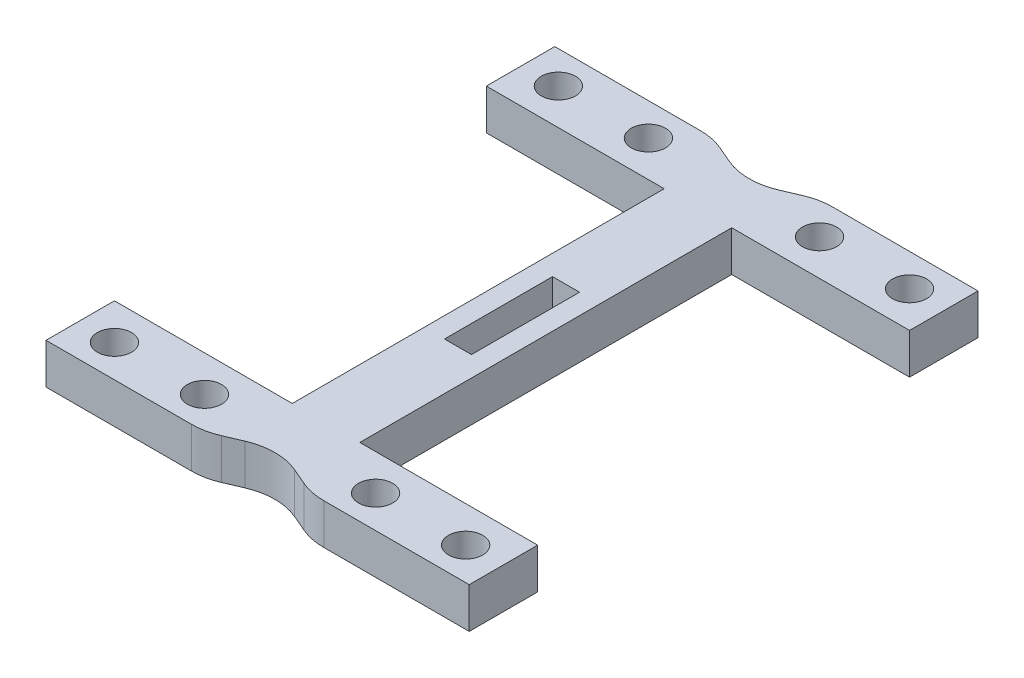
SolidWorks part; units mm, degrees
ref_plane "Front Plane" through (0, 0, 0) normal (0, 0, 1) x (1, 0, 0)
ref_plane "Top Plane" through (0, 0, 0) normal (0, 1, 0) x (1, 0, 0)
ref_plane "Right Plane" through (0, 0, 0) normal (1, 0, 0) x (0, 0, -1)
sketch "Sketch1" plane through (0, 0, 0) normal (0, 1, 0) x (1, 0, 0)
  line L0 (0, 3.6) -> (49, 3.6) construction
  line L1 (0, 0) -> (17.5879, 0)
  line L2 (0, 0) -> (0, 7.6)
  line L3 (0, 7.6) -> (19.75, 7.6)
  line L4 (47, 0) -> (47, 7.6)
  line L8 (29.4121, 0) -> (47, 0)
  line L9 (19.75, 7.6) -> (19.75, 28.25)
  line L15 (27.25, 28.25) -> (27.25, 7.6)
  line L16 (27.25, 7.6) -> (47, 7.6)
  line L17 (-0.2, 28.25) -> (47.2, 28.25) construction
  line L20 (19.75, 28.25) -> (22, 28.25)
  line L21 (17.5879, 0) -> (23.5, 2.5337)
  line L22 (23.5, 2.5337) -> (29.4121, 0)
  line L23 (19.75, 7.6) -> (27.25, 7.6) construction
  line L24 (23.5, 7.6) -> (23.5, 2.5337) construction
  line L25 (22, 28.25) -> (22, 22.25)
  line L26 (22, 22.25) -> (25, 22.25)
  line L27 (25, 22.25) -> (25, 28.25)
  line L28 (25, 28.25) -> (27.25, 28.25)
  circle A0 centre (4, 3.6) radius 1.9
  circle A1 centre (14, 3.6) radius 1.9
  circle A2 centre (33, 3.6) radius 1.9
  circle A3 centre (43, 3.6) radius 1.9
  dimension "D1" = 3.8
  dimension "D2" = 10
  dimension "D3" = 4
  dimension "D4" = 10
  dimension "D5" = 19
  dimension "D6" = 4
  dimension "D7" = 4
  dimension "D8" = 3.6
  dimension "D9" = 3
  dimension "D10" = 7.5
  dimension "D11" = 6
extrude "Boss-Extrude1" add sketch "Sketch1" along normal blind 4.5
mirror "Mirror1" about plane through (19.75, 4.5, -28.25) normal (0, 0, 1) of "Boss-Extrude1"
fillet "Fillet1" radius 7 6 edges at (29.4121, 2.25, -56.5) (17.5879, 2.25, -56.5) (23.5, 2.25, -53.9663) (17.5879, 2.25, 0) (29.4121, 2.25, 0) (23.5, 2.25, -2.5337)
